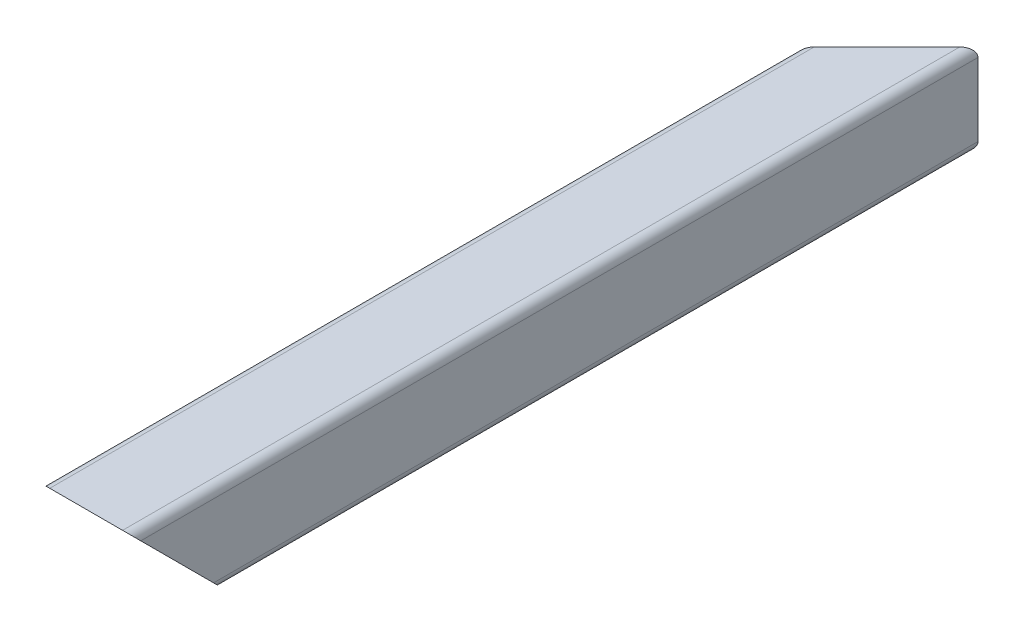
SolidWorks part; units mm, degrees
material "1.4305 (X8CrNiS18-9)"
ref_plane "Ön Düzlem" through (0, 0, 0) normal (0, 0, 1) x (1, 0, 0)
ref_plane "Üst Düzlem" through (0, 0, 0) normal (0, 1, 0) x (1, 0, 0)
ref_plane "Sağ Düzlem" through (0, 0, 0) normal (1, 0, 0) x (0, 0, -1)
sketch "Çizim1" plane through (0, 0, 0) normal (0, 0, 1) x (1, 0, 0)
  line L0 (-18, 16) -> (-18, -16)
  line L1 (-16, 20) -> (16, 20)
  line L2 (-20, 16) -> (-20, -16)
  line L3 (-16, -20) -> (16, -20)
  line L4 (20, 16) -> (20, -16)
  line L5 (-20, 20) -> (20, -20) construction
  line L6 (-20, -20) -> (20, 20) construction
  line L7 (-16, -18) -> (16, -18)
  line L8 (18, 16) -> (18, -16)
  line L9 (-16, 18) -> (16, 18)
  arc A0 (20, -16) -> (16, -20) centre (16, -16) cw
  arc A1 (16, 20) -> (20, 16) centre (16, 16) cw
  arc A2 (-16, 20) -> (-20, 16) centre (-16, 16) ccw
  arc A3 (-20, -16) -> (-16, -20) centre (-16, -16) ccw
  arc A4 (-18, -16) -> (-16, -18) centre (-16, -16) ccw
  arc A5 (18, -16) -> (16, -18) centre (16, -16) cw
  arc A6 (16, 18) -> (18, 16) centre (16, 16) cw
  arc A7 (-16, 18) -> (-18, 16) centre (-16, 16) ccw
  point P0 (0, 0)
  dimension "D3" = 4
  dimension "D1" = 40
  dimension "D2" = 40
  dimension "D4" = 2
extrude "Yükseklik-Ekstrüzyon1" add sketch "Çizim1" along normal blind 372
sketch "Çizim2" plane through (0, 0, 0) normal (0, 0, -1) x (-1, 0, 0)
  line L0 (-18.8284, 18.8284) -> (18.8284, -18.8284) construction
  arc A0 (-16, 20) -> (-20, 16) centre (-16, 16) ccw construction
  arc A1 (16, -20) -> (20, -16) centre (16, -16) ccw construction
sketch "Çizim3" plane through (0, 0, 0) normal (1, 0, 0) x (0, 0, -1)
  line L0 (-372, 20) -> (-332, -20)
  line L1 (-372, -20) -> (0, -20) construction
  line L2 (-332, -20) -> (-372, -20)
  line L3 (-372, -20) -> (-372, 20)
  dimension "D1" = 45
extrude "Kes-Ekstrüzyon1" cut sketch "Çizim3" against normal blind 43 and the other way blind 41
sketch "Çizim5" plane through (0, 0, 0) normal (0, 1, 0) x (1, 0, 0)
  line L0 (20, 0) -> (-20, -40)
  line L1 (-20, -368) -> (-20, 0) construction
  line L2 (-20, -40) -> (-20, 0)
  line L3 (-20, 0) -> (20, 0)
  dimension "D1" = 45
extrude "Kes-Ekstrüzyon2" cut sketch "Çizim5" against normal blind 61 and the other way blind 72
